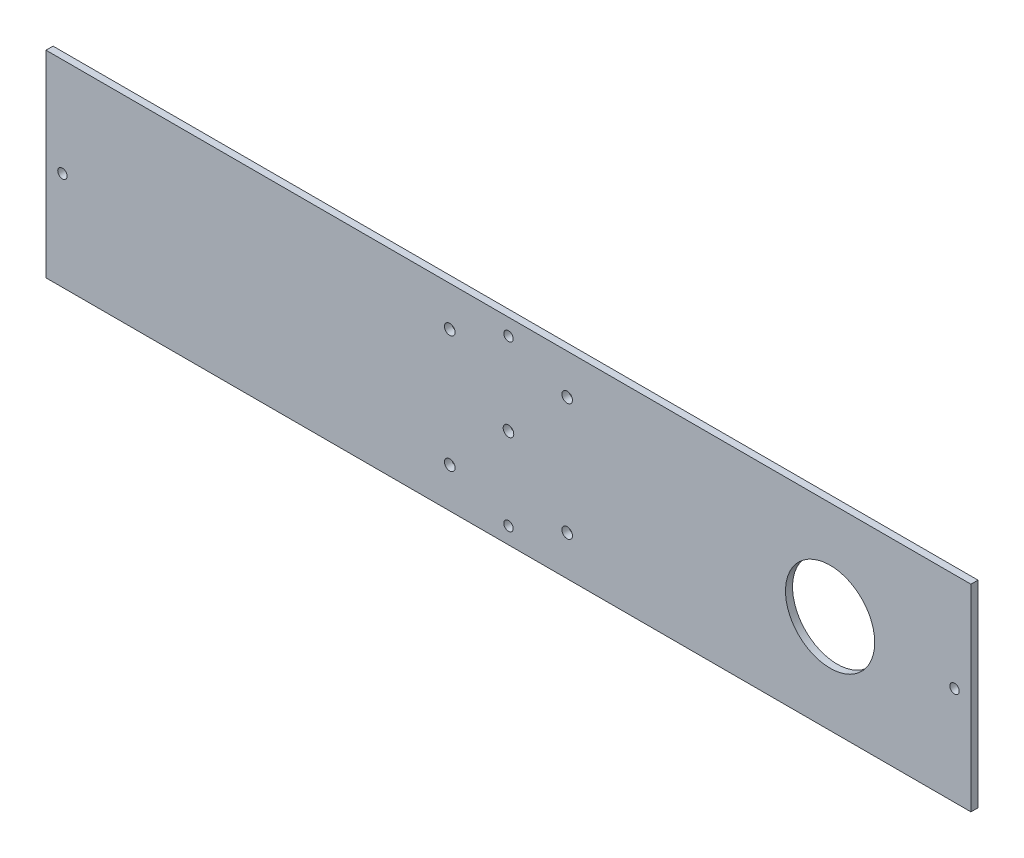
SolidWorks part; units mm, degrees
ref_plane "Piano frontale" through (0, 0, 0) normal (0, 0, 1) x (1, 0, 0)
ref_plane "Piano superiore" through (0, 0, 0) normal (0, 1, 0) x (1, 0, 0)
ref_plane "Piano destro" through (0, 0, 0) normal (1, 0, 0) x (0, 0, -1)
sketch "Schizzo1" plane through (0, 0, 0) normal (0, 0, 1) x (1, 0, 0)
  line L0 (0, 0) -> (0, 84)
  line L1 (0, 84) -> (394, 84)
  line L2 (394, 84) -> (394, 0)
  line L3 (394, 0) -> (0, 0)
  line L4 (0, 42) -> (394, 42) construction
  line L5 (197, 42) -> (197, 123.488) construction
  circle A0 centre (7, 42) radius 2
  circle A1 centre (197, 77) radius 2
  circle A2 centre (197, 7) radius 2
  circle A3 centre (387, 42) radius 2
  circle A4 centre (197, 42) radius 2.25
  circle A5 centre (172, 67) radius 2.25
  circle A6 centre (172, 17) radius 2.25
  circle A7 centre (222, 17) radius 2.25
  circle A8 centre (222, 67) radius 2.25
  circle A9 centre (334, 42) radius 19
  point P94 (173, 42)
  dimension "D3" = 7
  dimension "D4" = 7
  dimension "D6" = 4
  dimension "D5" = 4.5
  dimension "D16" = 38
  dimension "D1" = 84
  dimension "D2" = 394
  dimension "D13" = 50
  dimension "D14" = 50
  dimension "D15" = 7
  dimension "D17" = 60
extrude "Estrusione-Estrusione1" add sketch "Schizzo1" along normal blind 3
